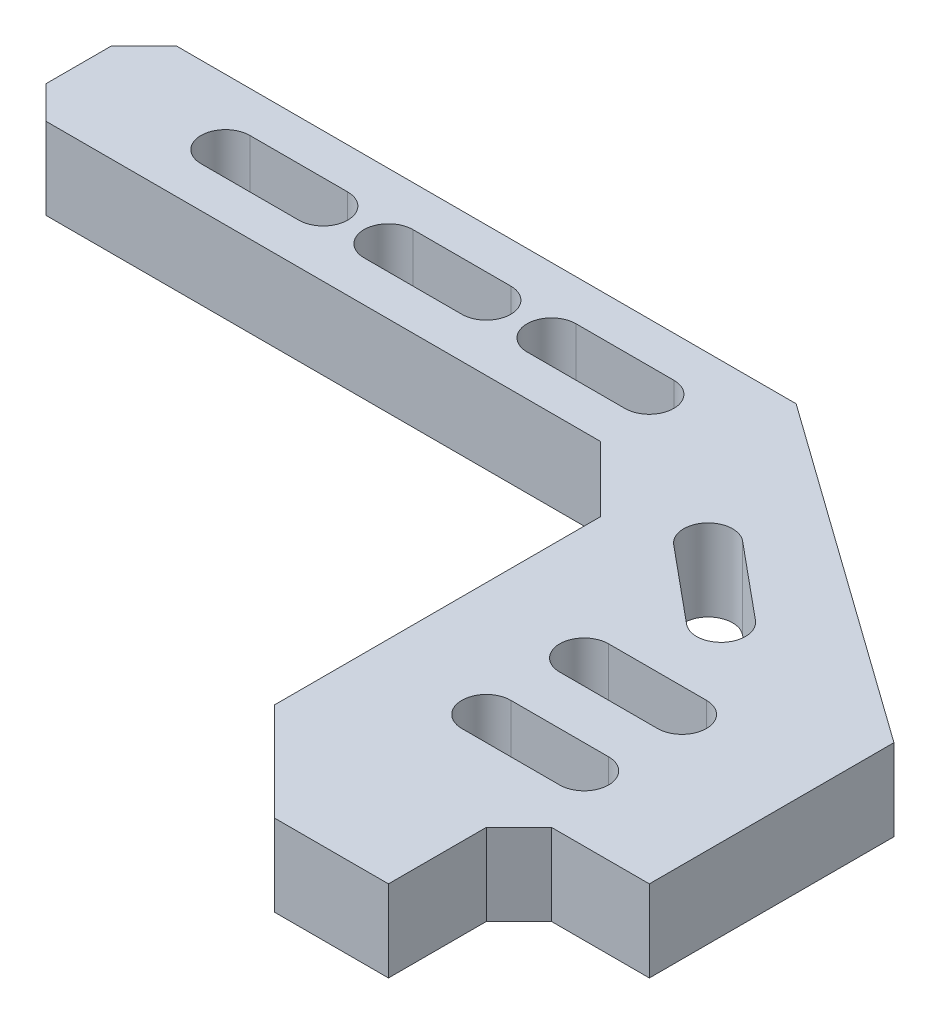
SolidWorks part; units mm, degrees
material "Plain Carbon Steel"
ref_plane "Front Plane" through (0, 0, 0) normal (0, 0, 1) x (1, 0, 0)
ref_plane "Top Plane" through (0, 0, 0) normal (0, 1, 0) x (1, 0, 0)
ref_plane "Right Plane" through (0, 0, 0) normal (1, 0, 0) x (0, 0, -1)
sketch "Sketch2" plane through (0, 0, 0) normal (0, 1, 0) x (1, 0, 0)
  line L0 (0, 0) -> (40.0263, 0)
  line L1 (40.0263, 0) -> (61.0263, -15)
  line L2 (61.0263, -15) -> (61.0263, -30)
  line L3 (61.0263, -30) -> (55.0263, -30)
  line L4 (53.0263, -32) -> (53.0263, -38)
  line L5 (53.0263, -38) -> (40.0263, -38)
  line L7 (40.0263, -38) -> (40.0263, -8)
  line L9 (40.0263, -8) -> (0.0263, -8)
  line L10 (0.0263, -8) -> (0.0263, 0)
  line L11 (0.0263, 0) -> (0, 0)
  line L12 (55.0263, -30) -> (53.0263, -32)
  line L13 (9.0263, -4) -> (15.0263, -4) construction
  line L14 (9.0263, -2.5) -> (15.0263, -2.5)
  line L15 (9.0263, -5.5) -> (15.0263, -5.5)
  line L16 (19.0263, -4) -> (25.0263, -4) construction
  line L17 (19.0263, -2.5) -> (25.0263, -2.5)
  line L18 (19.0263, -5.5) -> (25.0263, -5.5)
  line L19 (29.0263, -4) -> (35.0263, -4) construction
  line L20 (29.0263, -2.5) -> (35.0263, -2.5)
  line L21 (29.0263, -5.5) -> (35.0263, -5.5)
  line L22 (44.7168, -10.0853) -> (49.3358, -13.9147) construction
  line L23 (45.6741, -8.9305) -> (50.2932, -12.7599)
  line L24 (43.7594, -11.2401) -> (48.3785, -15.0695)
  line L25 (47.0263, -20) -> (53.0263, -20) construction
  line L26 (47.0263, -18.5) -> (53.0263, -18.5)
  line L27 (47.0263, -21.5) -> (53.0263, -21.5)
  line L28 (47.0263, -26) -> (53.0263, -26) construction
  line L29 (47.0263, -24.5) -> (53.0263, -24.5)
  line L30 (47.0263, -27.5) -> (53.0263, -27.5)
  line L31 (0.0263, -4) -> (45.6263, -4) construction
  arc A0 (9.0263, -2.5) -> (9.0263, -5.5) centre (9.0263, -4) ccw
  arc A1 (15.0263, -5.5) -> (15.0263, -2.5) centre (15.0263, -4) ccw
  arc A2 (19.0263, -2.5) -> (19.0263, -5.5) centre (19.0263, -4) ccw
  arc A3 (25.0263, -5.5) -> (25.0263, -2.5) centre (25.0263, -4) ccw
  arc A4 (29.0263, -2.5) -> (29.0263, -5.5) centre (29.0263, -4) ccw
  arc A5 (35.0263, -5.5) -> (35.0263, -2.5) centre (35.0263, -4) ccw
  arc A6 (45.6741, -8.9305) -> (43.7594, -11.2401) centre (44.7168, -10.0853) ccw
  arc A7 (48.3785, -15.0695) -> (50.2932, -12.7599) centre (49.3358, -13.9147) ccw
  arc A8 (47.0263, -18.5) -> (47.0263, -21.5) centre (47.0263, -20) ccw
  arc A9 (53.0263, -21.5) -> (53.0263, -18.5) centre (53.0263, -20) ccw
  arc A10 (47.0263, -24.5) -> (47.0263, -27.5) centre (47.0263, -26) ccw
  arc A11 (53.0263, -27.5) -> (53.0263, -24.5) centre (53.0263, -26) ccw
  point P2 (12.0263, -4)
  point P18 (22.0263, -4)
  point P26 (32.0263, -4)
  point P33 (47.0263, -12)
  point P40 (50.0263, -20)
  point P47 (50.0263, -26)
  point P56 (0, 0)
  point P57 (0, 0)
  point P58 (0, 0)
  dimension "D1" = 40
  dimension "D2" = 61.0263
  dimension "D3" = 13
  dimension "D4" = 40
  dimension "D5" = 8
  dimension "D6" = 30
  dimension "D7" = 15
  dimension "D8" = 30
  dimension "D9" = 6
  dimension "D10" = 2
  dimension "D11" = 2
  dimension "D12" = 9
  dimension "D13" = 6
  dimension "D14" = 3
  dimension "D15" = 4
  dimension "D16" = 4
  dimension "D17" = 7
  dimension "D18" = 12
  dimension "D19" = 10
  dimension "D20" = 4
  dimension "D21" = 10
extrude "Boss-Extrude1" add sketch "Sketch2" along normal blind 5 contours L12 L3 L2 L1 L0 L10 L9 L7 L5 L4 A11 L30 A10 L29 A9 L27 A8 L26 A7 L24 A6 L23 A5 L21 A4 L20 A3 L18 A2 L17 A1 L15 A0 L14
chamfer "Chamfer1" distance 2 angle 45 2 edges at (0.0263, 2.5, 0) (0.0263, 2.5, 8)
chamfer "Chamfer2" distance 6 angle 45 1 edges at (40.0263, 2.5, 38)
chamfer "Chamfer3" distance 4 angle 45 1 edges at (40.0263, 2.5, 8)
